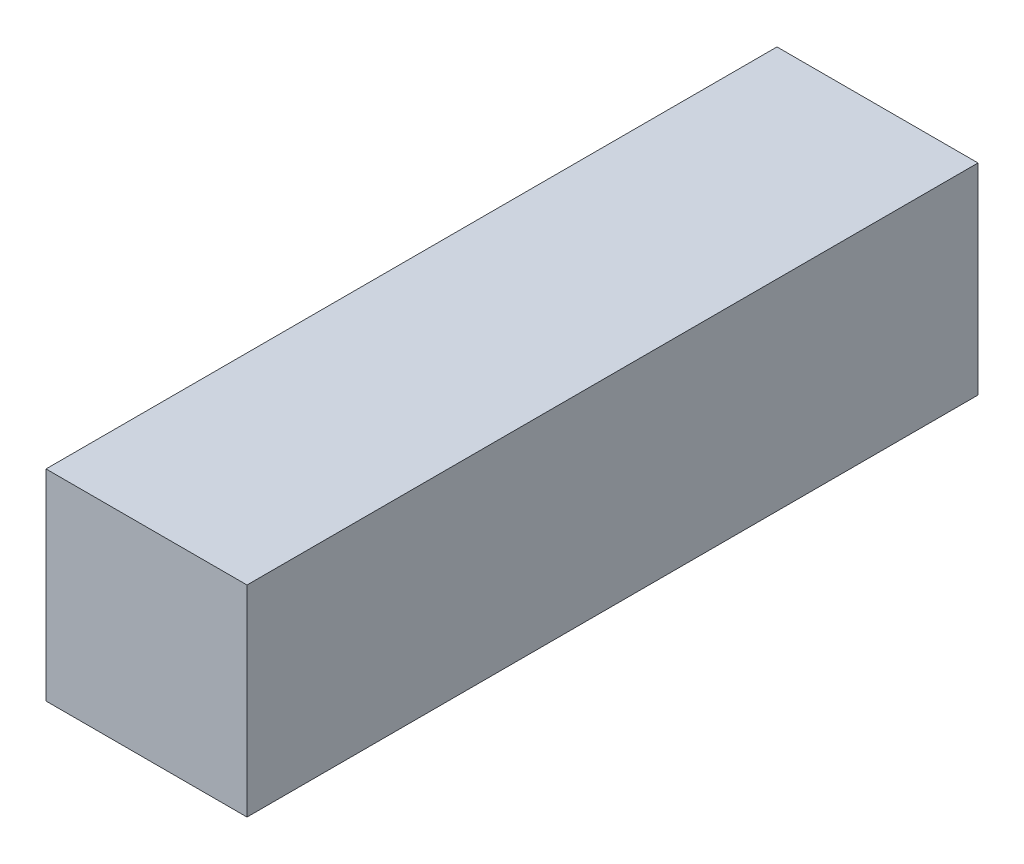
SolidWorks part; units mm, degrees
ref_plane "Front Plane" through (0, 0, 0) normal (0, 0, 1) x (1, 0, 0)
ref_plane "Top Plane" through (0, 0, 0) normal (0, 1, 0) x (1, 0, 0)
ref_plane "Right Plane" through (0, 0, 0) normal (1, 0, 0) x (0, 0, -1)
sketch "Sketch1" plane through (0, 0, 0) normal (0, 0, 1) x (1, 0, 0)
  line L1 (-11, 11) -> (11, 11)
  line L2 (-11, 11) -> (-11, -11)
  line L3 (-11, -11) -> (11, -11)
  line L4 (11, 11) -> (11, -11)
  line L5 (-11, 11) -> (11, -11) construction
  line L6 (-11, -11) -> (11, 11) construction
  point P0 (0, 0)
  dimension "D1" = 22
  dimension "D2" = 22
extrude "Boss-Extrude1" add sketch "Sketch1" along normal blind 80
